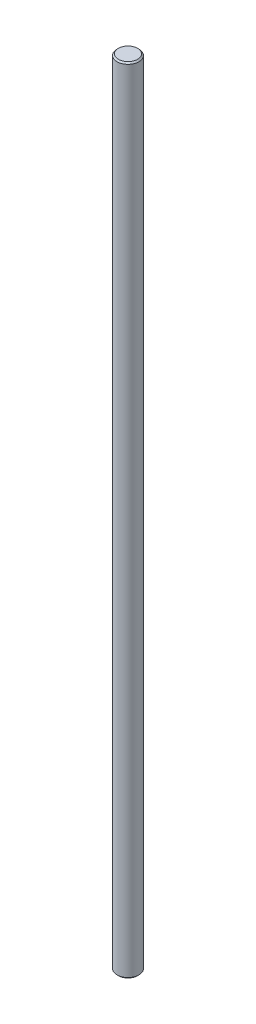
SolidWorks part; units mm, degrees
ref_plane "Front Plane" through (0, 0, 0) normal (0, 0, 1) x (1, 0, 0)
ref_plane "Top Plane" through (0, 0, 0) normal (0, 1, 0) x (1, 0, 0)
ref_plane "Right Plane" through (0, 0, 0) normal (1, 0, 0) x (0, 0, -1)
sketch "Sketch1" plane through (0, 0, 0) normal (0, 1, 0) x (1, 0, 0)
  circle A0 centre (0, 0) radius 4
  dimension "D1" = 8
extrude "Boss-Extrude1" add sketch "Sketch1" along normal mid plane 290
chamfer "Chamfer1" distance 0.5 angle 45 2 edges at (0, -145, 4) (0, 145, 4)
